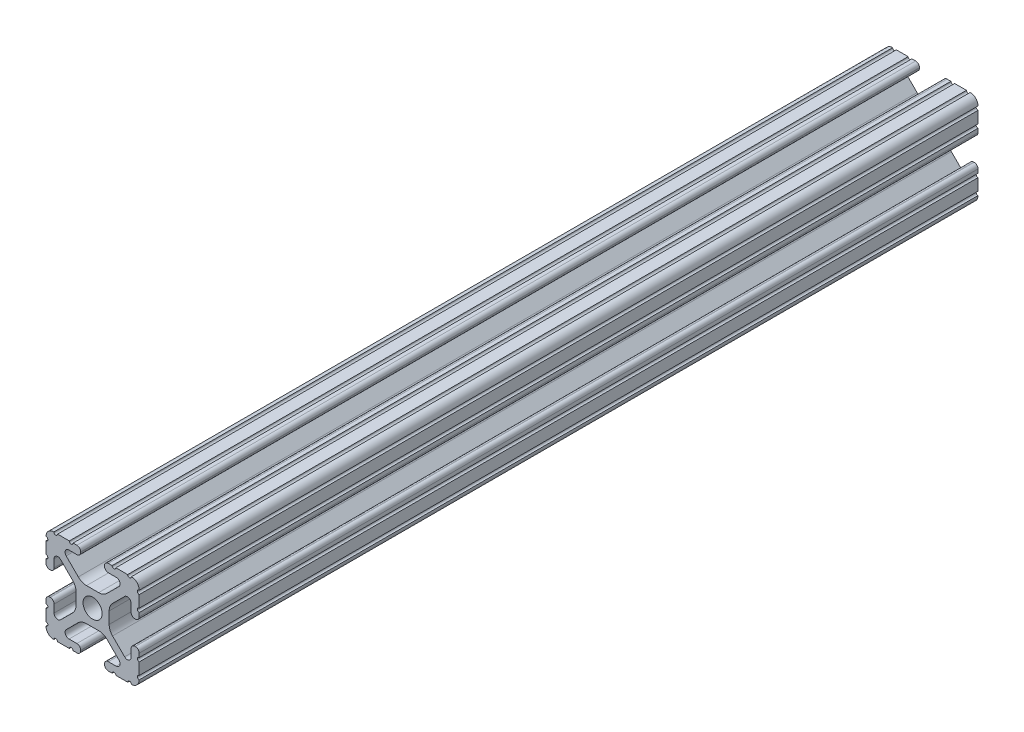
SolidWorks part; units mm, degrees
material "1060 Alloy"
ref_plane "Front Plane" through (0, 0, 0) normal (0, 0, 1) x (1, 0, 0)
ref_plane "Top Plane" through (0, 0, 0) normal (0, 1, 0) x (1, 0, 0)
ref_plane "Right Plane" through (0, 0, 0) normal (1, 0, 0) x (0, 0, -1)
sketch "Sketch1" plane through (0, 0, 0) normal (0, 0, 1) x (1, 0, 0)
  line L88 (-7.1797, -8.6452) -> (-3.9523, -5.4237)
  line L89 (-1.7093, -4.4958) -> (1.7093, -4.4958)
  line L90 (3.9523, -5.4237) -> (7.1797, -8.6452)
  line L91 (6.4164, -10.4902) -> (4.2875, -10.4902)
  line L92 (3.2385, -11.5392) -> (3.2385, -11.651)
  line L93 (4.2875, -12.7) -> (5.3171, -12.7)
  line L94 (6.3331, -12.7) -> (9.5504, -12.7)
  line L95 (12.7, -9.5504) -> (12.7, -6.3331)
  line L96 (12.7, -5.3171) -> (12.7, -4.2875)
  line L97 (11.651, -3.2385) -> (11.5392, -3.2385)
  line L98 (10.4902, -4.2875) -> (10.4902, -6.4021)
  line L99 (8.7371, -7.1294) -> (5.441, -3.8408)
  line L100 (4.5085, -1.5932) -> (4.5085, 1.5932)
  line L101 (5.441, 3.8408) -> (8.7371, 7.1294)
  line L102 (10.4902, 6.4021) -> (10.4902, 4.2875)
  line L103 (11.5392, 3.2385) -> (11.651, 3.2385)
  line L104 (12.7, 4.2875) -> (12.7, 5.3171)
  line L105 (12.7, 6.3331) -> (12.7, 9.5504)
  line L106 (9.5504, 12.7) -> (6.3331, 12.7)
  line L107 (5.3171, 12.7) -> (4.2875, 12.7)
  line L108 (3.2385, 11.651) -> (3.2385, 11.5392)
  line L109 (4.2875, 10.4902) -> (6.4768, 10.4902)
  line L110 (7.207, 8.7244) -> (3.8983, 5.4232)
  line L111 (1.6558, 4.4958) -> (-1.6558, 4.4958)
  line L112 (-3.8983, 5.4232) -> (-7.207, 8.7244)
  line L113 (-6.4768, 10.4902) -> (-4.2875, 10.4902)
  line L114 (-3.2385, 11.5392) -> (-3.2385, 11.651)
  line L115 (-4.2875, 12.7) -> (-5.3171, 12.7)
  line L116 (-6.3331, 12.7) -> (-9.5504, 12.7)
  line L117 (-12.7, 9.5504) -> (-12.7, 6.3331)
  line L118 (-12.7, 5.3171) -> (-12.7, 4.2875)
  line L119 (-11.651, 3.2385) -> (-11.5392, 3.2385)
  line L120 (-10.4902, 4.2875) -> (-10.4902, 6.4021)
  line L121 (-8.7371, 7.1294) -> (-5.441, 3.8408)
  line L122 (-4.5085, 1.5932) -> (-4.5085, -1.5932)
  line L123 (-5.441, -3.8408) -> (-8.7371, -7.1294)
  line L124 (-10.4902, -6.4021) -> (-10.4902, -4.2875)
  line L125 (-11.5392, -3.2385) -> (-11.651, -3.2385)
  line L126 (-12.7, -4.2875) -> (-12.7, -5.3171)
  line L127 (-12.7, -6.3331) -> (-12.7, -9.5504)
  line L128 (-9.5504, -12.7) -> (-6.3331, -12.7)
  line L129 (-5.3171, -12.7) -> (-4.2875, -12.7)
  line L130 (-3.2385, -11.651) -> (-3.2385, -11.5392)
  line L131 (-4.2875, -10.4902) -> (-6.4164, -10.4902)
  circle A1 centre (0, 0) radius 2.6035
  arc A104 (-7.1797, -8.6452) -> (-6.4164, -10.4902) centre (-6.4164, -9.4098) ccw
  arc A105 (-1.7093, -4.4958) -> (-3.9523, -5.4237) centre (-1.7093, -7.6708) ccw
  arc A106 (3.9523, -5.4237) -> (1.7093, -4.4958) centre (1.7093, -7.6708) ccw
  arc A107 (6.4164, -10.4902) -> (7.1797, -8.6452) centre (6.4164, -9.4098) ccw
  arc A108 (4.2875, -10.4902) -> (3.2385, -11.5392) centre (4.2875, -11.5392) ccw
  arc A109 (3.2385, -11.651) -> (4.2875, -12.7) centre (4.2875, -11.651) ccw
  arc A110 (6.3331, -12.7) -> (5.3171, -12.7) centre (5.8251, -12.7) ccw
  arc A111 (10.5664, -12.6998) -> (9.5504, -12.7) centre (10.0584, -12.7) ccw
  arc A112 (10.5664, -12.6998) -> (12.6998, -10.5664) centre (10.5918, -10.5918) ccw
  arc A113 (12.7, -9.5504) -> (12.6998, -10.5664) centre (12.7, -10.0584) ccw
  arc A114 (12.7, -5.3171) -> (12.7, -6.3331) centre (12.7, -5.8251) ccw
  arc A115 (12.7, -4.2875) -> (11.651, -3.2385) centre (11.651, -4.2875) ccw
  arc A116 (11.5392, -3.2385) -> (10.4902, -4.2875) centre (11.5392, -4.2875) ccw
  arc A117 (8.7371, -7.1294) -> (10.4902, -6.4021) centre (9.4628, -6.4021) ccw
  arc A118 (4.5085, -1.5932) -> (5.441, -3.8408) centre (7.6835, -1.5932) ccw
  arc A119 (5.441, 3.8408) -> (4.5085, 1.5932) centre (7.6835, 1.5932) ccw
  arc A120 (10.4902, 6.4021) -> (8.7371, 7.1294) centre (9.4628, 6.4021) ccw
  arc A121 (10.4902, 4.2875) -> (11.5392, 3.2385) centre (11.5392, 4.2875) ccw
  arc A122 (11.651, 3.2385) -> (12.7, 4.2875) centre (11.651, 4.2875) ccw
  arc A123 (12.7, 6.3331) -> (12.7, 5.3171) centre (12.7, 5.8251) ccw
  arc A124 (12.6998, 10.5664) -> (12.7, 9.5504) centre (12.7, 10.0584) ccw
  arc A125 (12.6998, 10.5664) -> (10.5664, 12.6998) centre (10.5918, 10.5918) ccw
  arc A126 (9.5504, 12.7) -> (10.5664, 12.6998) centre (10.0584, 12.7) ccw
  arc A127 (5.3171, 12.7) -> (6.3331, 12.7) centre (5.8251, 12.7) ccw
  arc A128 (4.2875, 12.7) -> (3.2385, 11.651) centre (4.2875, 11.651) ccw
  arc A129 (3.2385, 11.5392) -> (4.2875, 10.4902) centre (4.2875, 11.5392) ccw
  arc A130 (7.207, 8.7244) -> (6.4768, 10.4902) centre (6.4768, 9.4563) ccw
  arc A131 (1.6558, 4.4958) -> (3.8983, 5.4232) centre (1.6558, 7.6708) ccw
  arc A132 (-3.8983, 5.4232) -> (-1.6558, 4.4958) centre (-1.6558, 7.6708) ccw
  arc A133 (-6.4768, 10.4902) -> (-7.207, 8.7244) centre (-6.4768, 9.4563) ccw
  arc A134 (-4.2875, 10.4902) -> (-3.2385, 11.5392) centre (-4.2875, 11.5392) ccw
  arc A135 (-3.2385, 11.651) -> (-4.2875, 12.7) centre (-4.2875, 11.651) ccw
  arc A136 (-6.3331, 12.7) -> (-5.3171, 12.7) centre (-5.8251, 12.7) ccw
  arc A137 (-10.5664, 12.6998) -> (-9.5504, 12.7) centre (-10.0584, 12.7) ccw
  arc A138 (-10.5664, 12.6998) -> (-12.6998, 10.5664) centre (-10.5918, 10.5918) ccw
  arc A139 (-12.7, 9.5504) -> (-12.6998, 10.5664) centre (-12.7, 10.0584) ccw
  arc A140 (-12.7, 5.3171) -> (-12.7, 6.3331) centre (-12.7, 5.8251) ccw
  arc A141 (-12.7, 4.2875) -> (-11.651, 3.2385) centre (-11.651, 4.2875) ccw
  arc A142 (-11.5392, 3.2385) -> (-10.4902, 4.2875) centre (-11.5392, 4.2875) ccw
  arc A143 (-8.7371, 7.1294) -> (-10.4902, 6.4021) centre (-9.4628, 6.4021) ccw
  arc A144 (-4.5085, 1.5932) -> (-5.441, 3.8408) centre (-7.6835, 1.5932) ccw
  arc A145 (-5.441, -3.8408) -> (-4.5085, -1.5932) centre (-7.6835, -1.5932) ccw
  arc A146 (-10.4902, -6.4021) -> (-8.7371, -7.1294) centre (-9.4628, -6.4021) ccw
  arc A147 (-10.4902, -4.2875) -> (-11.5392, -3.2385) centre (-11.5392, -4.2875) ccw
  arc A148 (-11.651, -3.2385) -> (-12.7, -4.2875) centre (-11.651, -4.2875) ccw
  arc A149 (-12.7, -6.3331) -> (-12.7, -5.3171) centre (-12.7, -5.8251) ccw
  arc A150 (-12.6998, -10.5664) -> (-12.7, -9.5504) centre (-12.7, -10.0584) ccw
  arc A151 (-12.6998, -10.5664) -> (-10.5664, -12.6998) centre (-10.5918, -10.5918) ccw
  arc A152 (-9.5504, -12.7) -> (-10.5664, -12.6998) centre (-10.0584, -12.7) ccw
  arc A153 (-5.3171, -12.7) -> (-6.3331, -12.7) centre (-5.8251, -12.7) ccw
  arc A154 (-4.2875, -12.7) -> (-3.2385, -11.651) centre (-4.2875, -11.651) ccw
  arc A155 (-3.2385, -11.5392) -> (-4.2875, -10.4902) centre (-4.2875, -11.5392) ccw
extrude "Boss-Extrude1" add sketch "Sketch1" along normal mid plane 228.6
